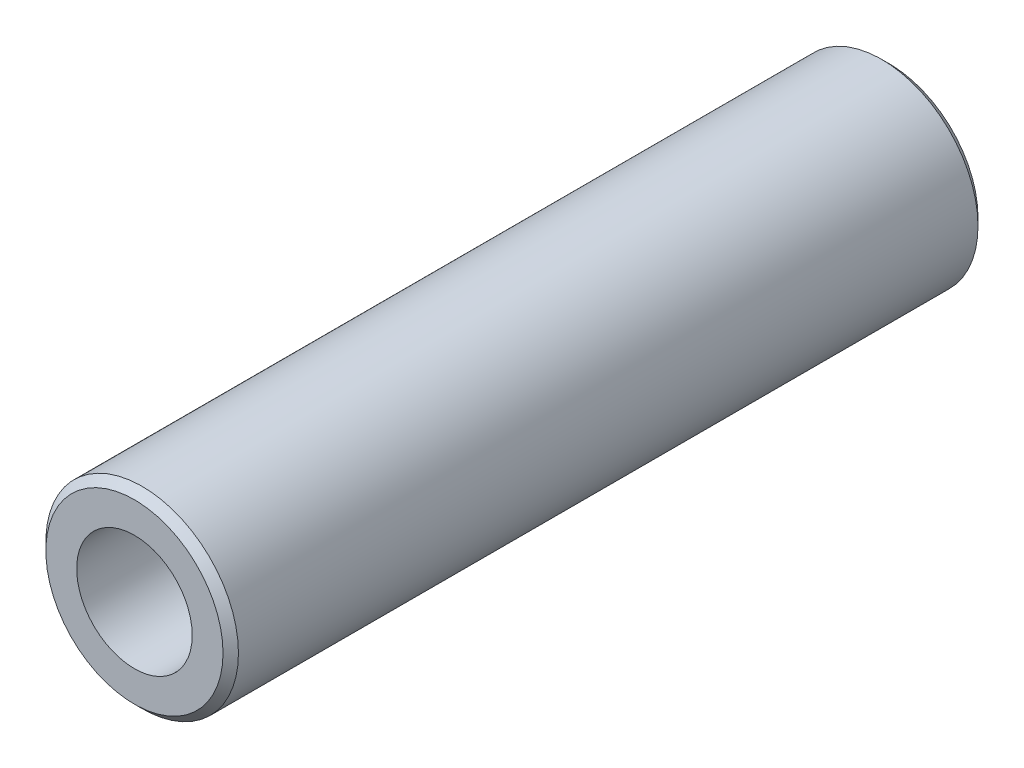
SolidWorks part; units mm, degrees
ref_plane "Front Plane" through (0, 0, 0) normal (0, 0, 1) x (1, 0, 0)
ref_plane "Top Plane" through (0, 0, 0) normal (0, 1, 0) x (1, 0, 0)
ref_plane "Right Plane" through (0, 0, 0) normal (1, 0, 0) x (0, 0, -1)
sketch "Sketch1" plane through (0, 0, 0) normal (0, 0, 1) x (1, 0, 0)
  circle A0 centre (0, 0) radius 6.25
  dimension "D1" = 12.5
extrude "Extrude-Thin1" add sketch "Sketch1" along normal mid plane 49 thin thin type one direction reverse wall 2.5
chamfer "Chamfer1" distance 0.5 angle 45 1 edges at (6.25, 0, 24.5)
chamfer "Chamfer2" distance 0.5 angle 45 1 edges at (6.25, 0, -24.5)
